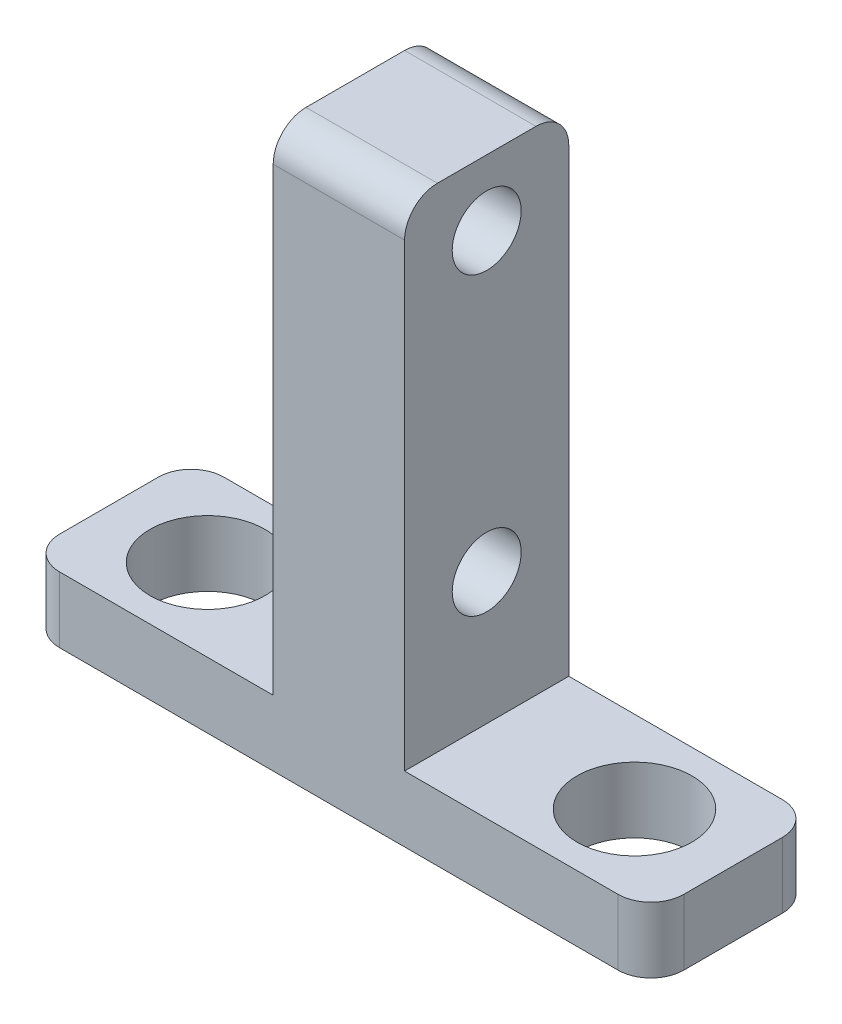
SolidWorks part; units mm, degrees
ref_plane "前视基准面" through (0, 0, 0) normal (0, 0, 1) x (1, 0, 0)
ref_plane "上视基准面" through (0, 0, 0) normal (0, 1, 0) x (1, 0, 0)
ref_plane "右视基准面" through (0, 0, 0) normal (1, 0, 0) x (0, 0, -1)
other "Configuration Table"
sketch "草图1" plane through (0, 0, 0) normal (0, 1, 0) x (1, 0, 0)
  line L1 (0, -5) -> (13, -5)
  line L3 (13, 0) -> (0, 0)
  line L4 (0, 0) -> (-3, 0)
  line L9 (-3, 0) -> (-3, -5)
  line L10 (-3, -5) -> (0, -5)
  line L11 (13, 0) -> (16, 0)
  line L12 (16, 0) -> (16, -5)
  line L13 (16, -5) -> (13, -5)
  dimension "D1" = 5
  dimension "D2" = 13
  dimension "D3" = 3
  dimension "D4" = 3
  dimension "D5" = 16
  dimension "D6" = 5
extrude "凸台-拉伸1" add sketch "草图1" along normal blind 2
sketch "草图2" plane through (0, 2, 0) normal (0, 1, 0) x (1, 0, 0)
  line L0 (-3, 0) -> (-3, -2.5) construction
  line L2 (-3, -2.5) -> (6.5, -2.5) construction
  line L8 (4.5, 0) -> (8.5, 0)
  line L9 (4.5, 0) -> (4.5, -5)
  line L10 (4.5, -5) -> (8.5, -5)
  line L11 (8.5, 0) -> (8.5, -5)
  line L12 (4.5, 0) -> (8.5, -5) construction
  line L13 (4.5, -5) -> (8.5, 0) construction
  line L14 (-3, -5) -> (16, -5) construction
  dimension "D1" = 5
  dimension "D2" = 4
  dimension "D3" = 4.5
  dimension "D4" = 4.5
extrude "凸台-拉伸2" add sketch "草图2" along normal blind 15
sketch "草图3" plane through (4.5, 0, 0) normal (-1, 0, 0) x (0, 0, 1)
  line L0 (5, 2) -> (5, 6) construction
  line L1 (5, 17) -> (5, 2) construction
  line L2 (5, 6) -> (2.5, 6) construction
  line L3 (2.5, 6) -> (2.5, 15) construction
  circle A0 centre (2.5, 15) radius 1.05
  circle A1 centre (2.5, 6) radius 1.05
  dimension "D4" = 2.1
  dimension "D5" = 2.1
  dimension "D1" = 4
  dimension "D2" = 2.5
  dimension "D3" = 9
extrude "切除-拉伸1" cut sketch "草图3" against normal blind 12
sketch "草图5" plane through (0, 2, 0) normal (0, 1, 0) x (1, 0, 0)
  line L0 (-3, 0) -> (-3, -2.5) construction
  line L1 (-3, 0) -> (-3, -5) construction
  line L2 (-3, -2.5) -> (0, -2.5) construction
  line L3 (16, 0) -> (16, -2.5) construction
  line L4 (16, -5) -> (16, 0) construction
  line L5 (16, -2.5) -> (13, -2.5) construction
  circle A0 centre (0, -2.5) radius 1.75
  circle A1 centre (13, -2.5) radius 1.75
  dimension "D2" = 3.5
  dimension "D3" = 3
  dimension "D4" = 3.5
  dimension "D1" = 3
extrude "切除-拉伸2" cut sketch "草图5" against normal blind 12
fillet "圆角1" radius 1 4 edges at (-3, 1, 0) (-3, 1, 5) (16, 1, 5) (16, 1, 0)
fillet "圆角2" radius 1 2 edges at (6.5, 17, 0) (6.5, 17, 5)
